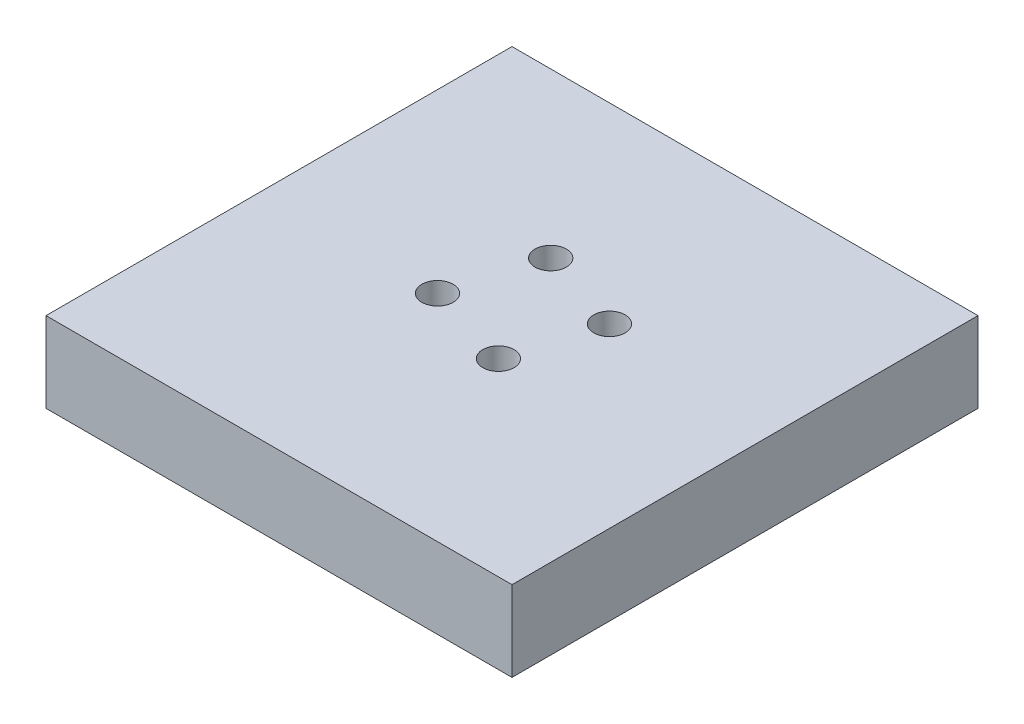
SolidWorks part; units mm, degrees
ref_plane "Front Plane" through (0, 0, 0) normal (0, 0, 1) x (1, 0, 0)
ref_plane "Top Plane" through (0, 0, 0) normal (0, 1, 0) x (1, 0, 0)
ref_plane "Right Plane" through (0, 0, 0) normal (1, 0, 0) x (0, 0, -1)
sketch "Sketch1" plane through (0, 0, 0) normal (0, 1, 0) x (1, 0, 0)
  line L1 (-29, -29) -> (29, -29)
  line L2 (-29, -29) -> (-29, 29)
  line L3 (-29, 29) -> (29, 29)
  line L4 (29, -29) -> (29, 29)
  line L5 (-29, -29) -> (29, 29) construction
  line L6 (-29, 29) -> (29, -29) construction
  point P0 (0, 0)
  dimension "D1" = 58
  dimension "D2" = 58
extrude "Boss-Extrude1" add sketch "Sketch1" along normal blind 10
sketch "Sketch2" plane through (-29, 0, 0) normal (-1, 0, 0) x (0, 0, 1)
  line L0 (-29, 10) -> (-29, 0) construction
  circle A0 centre (0, 5) radius 2.5
  point P7 (-29, 5)
  dimension "D1" = 5
extrude "Cut-Extrude1" cut sketch "Sketch2" against normal blind 10
sketch "Sketch7" plane through (0, 10, 0) normal (0, 1, 0) x (1, 0, 0)
  circle A0 centre (-3.7915, 8.6061) radius 1.95
  circle A1 centre (6.9552, 5.176) radius 1.95
  circle A3 centre (-7.0445, -2.2299) radius 1.95
  circle A5 centre (3.7915, -5.4829) radius 1.95
extrude "Cut-Extrude4" cut sketch "Sketch7" against normal through all
sketch "Sketch4" plane through (0, 0, 0) normal (0, -1, 0) x (1, 0, 0)
  circle A0 centre (-12.2302, 12.6132) radius 3.7428
  circle A1 centre (12.6132, 12.2302) radius 3.7428
  circle A2 centre (12.2302, -12.6132) radius 3.7428
  circle A3 centre (-12.6132, -12.2302) radius 3.7428
  point P11 (0, 0)
  dimension "D1" = 4
